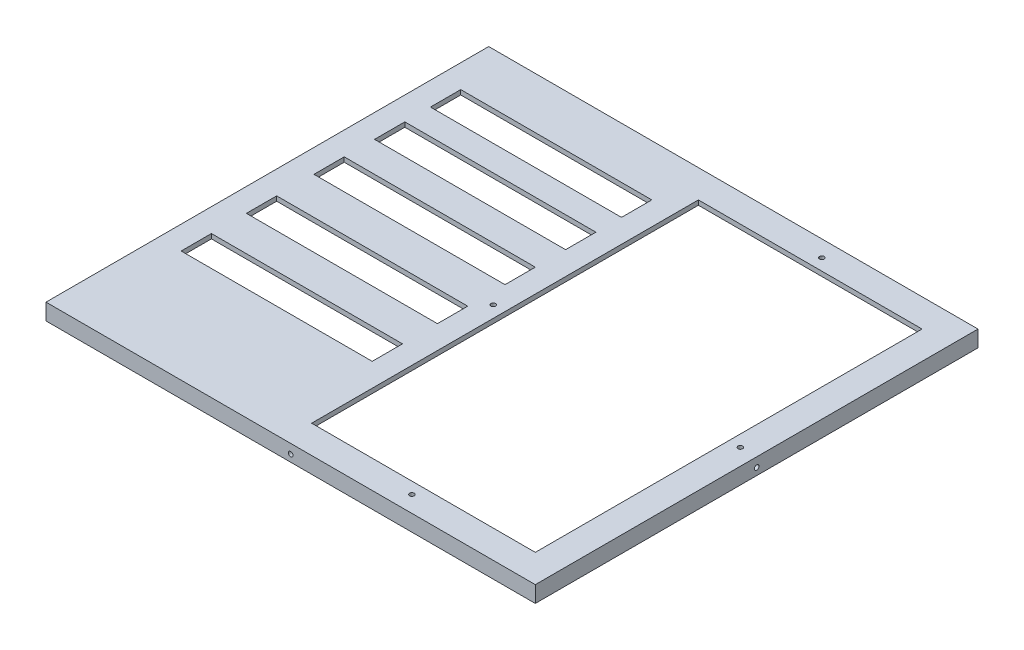
SolidWorks part; units mm, degrees
ref_plane "Front Plane" through (0, 0, 0) normal (0, 0, 1) x (1, 0, 0)
ref_plane "Top Plane" through (0, 0, 0) normal (0, 1, 0) x (1, 0, 0)
ref_plane "Right Plane" through (0, 0, 0) normal (1, 0, 0) x (0, 0, -1)
sketch "Sketch1" plane through (0, 0, 0) normal (0, 1, 0) x (1, 0, 0)
  line L1 (-103, 93) -> (103, 93)
  line L2 (-103, 93) -> (-103, -93)
  line L3 (-103, -93) -> (103, -93)
  line L4 (103, 93) -> (103, -93)
  line L5 (-103, 93) -> (103, -93) construction
  line L6 (-103, -93) -> (103, 93) construction
  line L7 (-105, 95) -> (105, 95)
  line L8 (-105, 95) -> (-105, -95)
  line L9 (-105, -95) -> (105, -95)
  line L10 (105, 95) -> (105, -95)
  line L11 (-105, 95) -> (105, -95) construction
  line L12 (-105, -95) -> (105, 95) construction
  point P0 (0, 0)
  point P6 (0, 0)
  dimension "D1" = 210
  dimension "D2" = 190
extrude "Boss-Extrude1" add sketch "Sketch1" along normal blind 5
sketch "Sketch5" plane through (-105, 0, 0) normal (-1, 0, 0) x (0, 0, 1)
  line L0 (-95, 0) -> (95, 0) construction
  circle A0 centre (0, 3) radius 1
  point P4 (0, 0)
  dimension "D1" = 3
sketch "Sketch6" plane through (0, 0, -95) normal (0, 0, -1) x (-1, 0, 0)
  line L0 (-105, 0) -> (105, 0) construction
  circle A1 centre (0, 3) radius 1
  point P4 (0, 0)
  dimension "D1" = 3
sketch "Sketch7" plane through (105, 0, 0) normal (1, 0, 0) x (0, 0, -1)
  line L0 (-95, 0) -> (95, 0) construction
  circle A0 centre (0, 3) radius 1
  point P4 (0, 0)
  dimension "D1" = 3
sketch "Sketch8" plane through (0, 0, 95) normal (0, 0, 1) x (1, 0, 0)
  line L0 (-105, 0) -> (105, 0) construction
  circle A0 centre (0, 3) radius 1
  dimension "D1" = 3
extrude "Cut-Extrude1" cut sketch "Sketch7" against normal blind 2
extrude "Cut-Extrude2" cut sketch "Sketch8" against normal blind 2
extrude "Cut-Extrude3" cut sketch "Sketch6" against normal blind 2
extrude "Cut-Extrude4" cut sketch "Sketch5" against normal blind 2
sketch "Sketch9" plane through (0, 5, 0) normal (0, 1, 0) x (1, 0, 0)
  line L0 (-95, 93) -> (-95, -93) construction
  line L1 (105, -95) -> (-105, -95)
  line L2 (105, -95) -> (105, 95)
  line L3 (105, 95) -> (-105, 95)
  line L4 (-105, -95) -> (-105, 95)
  line L5 (105, -95) -> (-105, 95) construction
  line L6 (105, 95) -> (-105, -95) construction
  line L7 (103, 93) -> (-103, 93) construction
  line L8 (-103, -93) -> (103, -93) construction
  line L10 (-103, 93) -> (-103, -93) construction
  line L11 (-3, 83) -> (93, 83)
  line L12 (-95, -47) -> (-13, -47)
  line L13 (-95, -47) -> (-95, -34)
  line L14 (-95, -34) -> (-13, -34)
  line L15 (-13, -47) -> (-13, -34)
  line L16 (-95, -19) -> (-13, -19)
  line L17 (-95, -19) -> (-95, -6)
  line L18 (-95, -6) -> (-13, -6)
  line L19 (-13, -19) -> (-13, -6)
  line L20 (-95, 10) -> (-13, 10)
  line L21 (-95, 10) -> (-95, 23)
  line L22 (-95, 23) -> (-13, 23)
  line L23 (-13, 10) -> (-13, 23)
  line L24 (-95, 36) -> (-13, 36)
  line L25 (-95, 36) -> (-95, 49)
  line L26 (-95, 49) -> (-13, 49)
  line L27 (-13, 36) -> (-13, 49)
  line L28 (-95, 73) -> (-13, 73)
  line L29 (-95, 73) -> (-95, 60)
  line L30 (-95, 60) -> (-13, 60)
  line L31 (-13, 73) -> (-13, 60)
  line L32 (93, 83) -> (93, -83)
  line L33 (93, -83) -> (-3, -83)
  line L34 (-3, -83) -> (-3, 83)
  line L35 (103, -93) -> (103, 93) construction
  circle A0 centre (98, 0) radius 1
  circle A1 centre (45, 88) radius 1
  circle A2 centre (-8, 0) radius 1
  circle A3 centre (45, -88) radius 1
  point P0 (0, 0)
  point P14 (-95, -47)
  point P15 (-95, -49)
  point P16 (-95, 10)
  point P17 (-95, 6)
  point P18 (-95, 73)
  point P47 (93, 0)
  point P50 (45, 83)
  dimension "D11" = 5
  dimension "D12" = 5
  dimension "D13" = 5
  dimension "D14" = 5
  dimension "D1" = 8
  dimension "D2" = 20
  dimension "D3" = 44
  dimension "D4" = 70
  dimension "D5" = 99
  dimension "D6" = 127
  dimension "D7" = 10
  dimension "D8" = 10
  dimension "D9" = 100
  dimension "D10" = 10
  dimension "D15" = 166
  dimension "D16" = 96
extrude "Boss-Extrude3" add sketch "Sketch9" along normal blind 2
